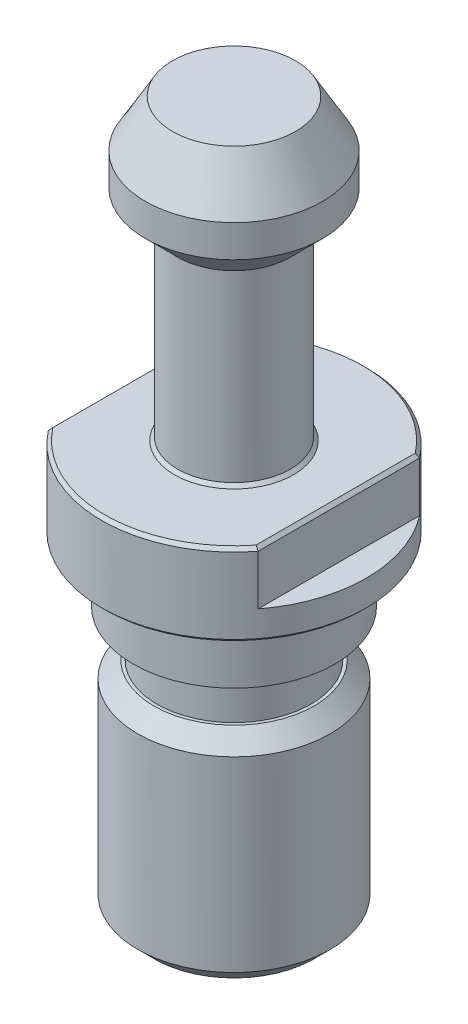
SolidWorks part; units mm, degrees
material "Cast Carbon Steel"
ref_plane "Front Plane" through (0, 0, 0) normal (0, 0, 1) x (1, 0, 0)
ref_plane "Top Plane" through (0, 0, 0) normal (0, 1, 0) x (1, 0, 0)
ref_plane "Right Plane" through (0, 0, 0) normal (1, 0, 0) x (0, 0, -1)
sketch "Sketch1" plane through (0, 0, 0) normal (0, 0, 1) x (1, 0, 0)
  line L0 (0, 0) -> (0, 65.5516) construction
  line L1 (0, 0) -> (5.975, 0)
  line L2 (5.975, 0) -> (5.975, 13.6)
  line L3 (5.975, 13.6) -> (4.785, 13.6)
  line L4 (4.785, 13.6) -> (4.785, 16.5)
  line L5 (4.785, 16.5) -> (6.265, 16.5)
  line L6 (6.265, 16.5) -> (6.265, 20.3)
  line L7 (6.265, 20.3) -> (8.22, 20.3)
  line L8 (8.22, 20.3) -> (8.22, 25.4)
  line L9 (8.22, 25.4) -> (3.5, 25.4)
  line L10 (3.5, 25.4) -> (3.5, 37)
  line L11 (3.5, 37) -> (5.5, 39)
  line L12 (5.5, 39) -> (5.5, 41)
  line L13 (5.5, 41) -> (3.8141, 43.92)
  line L14 (3.8141, 43.92) -> (0, 43.92)
  line L15 (0, 0) -> (0, 43.92)
other "AlignGroup2" parameters "D2"=12.2932, "D1"=124.277, "D3"=21.1209, "D4"=13.1194, "D5"=12.4805, "D6"=14.5597, "D7"=20.3199, "D8"=8, "D9"=42, "D10"=15, "D11"=2.8263, "D12"=5.1, "D13"=3.8, "D14"=2.9, "D15"=13.6, "D16"=2.7015
revolve "Revolve1" add sketch "Sketch1" angle 360 about L0
chamfer "Chamfer1" distance 1 angle 45 2 edges at (0, 13.6, -5.975) (0, 0, -5.975)
sketch "Sketch2" plane through (0, 25.4, 0) normal (0, 1, 0) x (1, 0, 0)
  line L1 (6.515, -5.0123) -> (-6.515, -5.0123) construction
  line L2 (6.515, -5.0123) -> (6.515, 5.0123)
  line L3 (6.515, 5.0123) -> (-6.515, 5.0123) construction
  line L4 (-6.515, -5.0123) -> (-6.515, 5.0123)
  line L5 (6.515, -5.0123) -> (-6.515, 5.0123) construction
  line L6 (6.515, 5.0123) -> (-6.515, -5.0123) construction
  circle A0 centre (0, 0) radius 8.22 construction
  arc A1 (6.515, 5.0123) -> (-6.515, 5.0123) centre (0, 0) ccw
  circle A2 centre (0, 0) radius 8.22
  arc A3 (-6.515, -5.0123) -> (6.515, -5.0123) centre (0, 0) ccw
  point P0 (0, 0)
  dimension "D1" = 13.03
  dimension "D2" = 0
extrude "Cut-Extrude1" cut sketch "Sketch2" against normal blind 3.3 flip side to cut
chamfer "Chamfer2" distance 0.2 angle 45 7 edges at (0, 20.3, -6.265) (0, 20.3, -8.22) (-6.515, 25.4, 0) (0, 25.4, 8.22) (0, 25.4, -8.22) (6.515, 25.4, 0) (0, 25.4, -3.5)
